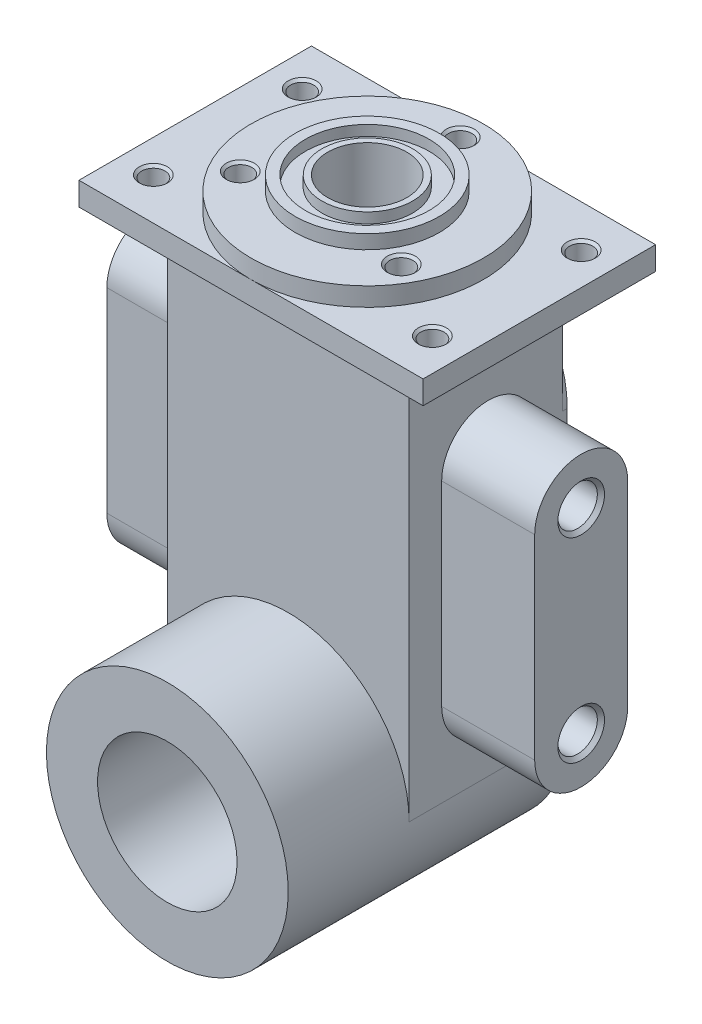
SolidWorks part; units mm, degrees
ref_plane "前视基准面" through (0, 0, 0) normal (0, 0, 1) x (1, 0, 0)
ref_plane "上视基准面" through (0, 0, 0) normal (0, 1, 0) x (1, 0, 0)
ref_plane "右视基准面" through (0, 0, 0) normal (1, 0, 0) x (0, 0, -1)
sketch "草图1" plane through (0, 0, 0) normal (0, 0, 1) x (1, 0, 0)
  line L0 (0, 0) -> (0, 60) construction
  line L1 (0, -55) -> (0, 55) construction
  line L2 (-26, 0) -> (-26, 60)
  line L3 (26, 0) -> (26, 60)
  arc A0 (-26, 0) -> (26, 0) centre (0, 0) ccw
  arc A1 (26, 60) -> (-26, 60) centre (0, 60) ccw
  point P5 (0, 30)
  dimension "D1" = 52
  dimension "D2" = 60
extrude "凸台-拉伸1" add sketch "草图1" along normal blind 34
sketch "草图3" plane through (0, 0, 0) normal (0, 0, 1) x (1, 0, 0)
  line L1 (-26, 60) -> (26, 60)
  line L2 (-26, 60) -> (-26, 87)
  line L3 (-26, 87) -> (26, 87)
  line L4 (26, 60) -> (26, 87)
  arc A0 (26, 60) -> (-26, 60) centre (0, 60) ccw construction
  point P4 (0, 0)
  dimension "D1" = 27
sketch "草图4" plane through (0, 0, 0) normal (0, 1, 0) x (1, 0, 0)
  line L0 (0, -18.7) -> (0, 18.7) construction
  line L1 (-37, -42) -> (37, -42)
  line L2 (-37, -42) -> (-37, 8)
  line L3 (-37, 8) -> (37, 8)
  line L4 (37, -42) -> (37, 8)
  line L5 (-37, -42) -> (37, 8) construction
  line L6 (-37, 8) -> (37, -42) construction
  line L7 (-26, 0) -> (26, 0) construction
  point P0 (0, -17)
  dimension "D1" = 74
  dimension "D2" = 50
  dimension "D3" = 17
extrude "凸台-拉伸2" add sketch "草图4" along normal blind 5 from offset 87 separate body
sketch "草图5" plane through (0, 92, 0) normal (0, 1, 0) x (1, 0, 0)
  line L0 (0, -37.4) -> (0, 37.4) construction
  line L1 (37, 8) -> (-37, 8) construction
  line L2 (-37, -42) -> (37, -42) construction
  circle A0 centre (0, -17) radius 25
extrude "凸台-拉伸3" add sketch "草图5" along normal blind 4
sketch "草图6" plane through (0, 96, 0) normal (0, 1, 0) x (1, 0, 0)
  circle A0 centre (0, -17) radius 15.5
  dimension "D1" = 31
extrude "凸台-拉伸4" add sketch "草图6" along normal blind 3
sketch "草图7" plane through (0, 0, 0) normal (1, 0, 0) x (0, 0, -1)
  line L0 (-17, 60) -> (-17, 18) construction
  line L1 (0, 50.6) -> (0, -50.6) construction
  line L2 (-27, 60) -> (-27, 18)
  line L3 (-7, 60) -> (-7, 18)
  line L4 (-34, 60) -> (0, 60) construction
  arc A0 (-27, 60) -> (-7, 60) centre (-17, 60) cw
  arc A1 (-27, 18) -> (-7, 18) centre (-17, 18) ccw
  dimension "D1" = 42
  dimension "D2" = 17
  dimension "D3" = 10
  dimension "D4" = 10
extrude "凸台-拉伸5" add sketch "草图7" along normal mid plane 92
sketch "草图8" plane through (0, 0, 34) normal (0, 0, 1) x (1, 0, 0)
  line L0 (-37, 87) -> (37, 87) construction
  line L1 (-26, 60) -> (26, 60)
  line L2 (-26, 60) -> (-26, 87)
  line L3 (-26, 87) -> (26, 87)
  line L4 (26, 60) -> (26, 87)
  arc A0 (26, 60) -> (-26, 60) centre (0, 60) ccw construction
  point P7 (26, 60)
extrude "凸台-拉伸6" add sketch "草图8" against normal blind 33
sketch "草图9" plane through (0, 0, 34) normal (0, 0, 1) x (1, 0, 0)
  circle A0 centre (0, 0) radius 26
  dimension "D1" = 52
extrude "凸台-拉伸7" add sketch "草图9" along normal blind 60 from surface at -34 starting at face at (0, 30, 0)
sketch "草图10" plane through (0, 0, 0) normal (0, 0, -1) x (-1, 0, 0)
  line L0 (0, 0) -> (0, 60) construction
  line L1 (-16, 0) -> (-16, 60)
  line L2 (16, 0) -> (16, 60)
  arc A0 (-16, 0) -> (16, 0) centre (0, 0) ccw
  arc A1 (16, 60) -> (-16, 60) centre (0, 60) ccw
  point P4 (0, 30)
extrude "切除-拉伸1" cut sketch "草图10" against normal blind 30
sketch "草图11" plane through (0, 0, 60) normal (0, 0, 1) x (1, 0, 0)
  circle A0 centre (0, 0) radius 15
  dimension "D1" = 30
extrude "切除-拉伸2" cut sketch "草图11" against normal through all
sketch "草图12" plane through (0, 99, 0) normal (0, 1, 0) x (1, 0, 0)
  circle A0 centre (0, -17) radius 8.5
  dimension "D1" = 17
extrude "切除-拉伸3" cut sketch "草图12" against normal up to next
sketch "草图13" plane through (0, 99, 0) normal (0, 1, 0) x (1, 0, 0)
  circle A0 centre (0, -17) radius 9.75
  circle A1 centre (0, -17) radius 13.3
  dimension "D1" = 19.5
  dimension "D2" = 26.6
extrude "切除-拉伸4" cut sketch "草图13" against normal blind 2.25
sketch "草图14" plane through (0, 96, 0) normal (0, 1, 0) x (1, 0, 0)
  circle A0 centre (0, -17) radius 20 construction
  point P3 (0, 3)
  dimension "D1" = 40
hole_wizard "M6 螺纹孔1" positions "草图14" profile "草图15" tap size "M6" standard "GB" end condition up to next
sketch "草图15" plane through (0, 96, -3) normal (1, 0, 0) x (0, 0, 1)
  line L0 (0, 0) -> (0, 9)
  line L1 (0, 9) -> (2.5, 9)
  line L2 (2.5, 9) -> (2.5, 0.525)
  line L3 (2.5, 0.525) -> (3.025, 0)
  line L5 (3.025, 0) -> (0, 0)
  line L6 (-2.5, 0.525) -> (-3.025, 0) construction
  line L11 (0, -6.35) -> (0, 107.95) construction
  dimension "通孔螺纹孔钻头直径" = 5
  dimension "通孔螺纹孔钻头深度" = 9
  dimension "近端锥形沉头孔直径" = 6.05
  dimension "近端锥形沉头孔角度" = 90
cosmetic thread "孔螺纹线1" parameters "D2"=6
sketch "草图16" plane through (0, 96, 0) normal (0, 1, 0) x (1, 0, 0)
  line L0 (-17.3205, -27) -> (0, -17) construction
  line L1 (0, -17) -> (17.3205, -27) construction
  line L2 (-17.3205, -27) -> (17.3205, -27) construction
  circle A0 centre (0, -17) radius 20 construction
  point P3 (-17.3205, -27)
  point P4 (17.3205, -27)
  dimension "D1" = 40
  dimension "D2" = 120
hole_wizard "M6 螺纹孔2" positions "草图16" profile "草图17" tap size "M6" standard "GB"
sketch "草图17" plane through (17.3205, 96, 27) normal (1, 0, 0) x (0, 0, 1)
  line L0 (0, 0) -> (0, 16)
  line L1 (0, 16) -> (2.5, 14.4978)
  line L2 (2.5, 14.4978) -> (2.5, 0.525)
  line L3 (2.5, 0.525) -> (3.025, 0)
  line L5 (3.025, 0) -> (0, 0)
  line L6 (-2.5, 0.525) -> (-3.025, 0) construction
  line L10 (0, 16) -> (-2.5, 14.4978) construction
  line L11 (0, -6.35) -> (0, 107.95) construction
  dimension "螺纹孔钻头直径" = 5
  dimension "螺纹孔钻头深度" = 16
  dimension "近端锥形沉头孔直径" = 6.05
  dimension "近端锥形沉头孔角度" = 90
  dimension "导头角度" = 118
cosmetic thread "孔螺纹线2" parameters "D1"=12, "D2"=6
cosmetic thread "孔螺纹线3" parameters "D1"=12, "D2"=6
sketch "草图18" plane through (0, 92, 0) normal (0, 1, 0) x (1, 0, 0)
  line L0 (0, -37.4) -> (0, 37.4) construction
  line L1 (-30, -33) -> (30, -33) construction
  line L2 (-30, -33) -> (-30, -1) construction
  line L3 (-30, -1) -> (30, -1) construction
  line L4 (30, -33) -> (30, -1) construction
  line L5 (-30, -33) -> (30, -1) construction
  line L6 (-30, -1) -> (30, -33) construction
  circle A0 centre (0, -17) radius 15.5 construction
  point P0 (0, -17)
  point P10 (-30, -1)
  point P11 (-30, -33)
  point P12 (30, -33)
  point P13 (30, -1)
  dimension "D1" = 32
  dimension "D2" = 60
hole_wizard "M6 螺纹孔3" positions "草图18" profile "草图19" tap size "M6" standard "GB" end condition up to next
sketch "草图19" plane through (30, 92, 1) normal (1, 0, 0) x (0, 0, 1)
  line L0 (0, 0) -> (0, 5)
  line L1 (0, 5) -> (2.5, 5)
  line L2 (2.5, 5) -> (2.5, 0.525)
  line L3 (2.5, 0.525) -> (3.025, 0)
  line L5 (3.025, 0) -> (0, 0)
  line L6 (-2.5, 0.525) -> (-3.025, 0) construction
  line L11 (0, -6.35) -> (0, 107.95) construction
  dimension "通孔螺纹孔钻头直径" = 5
  dimension "通孔螺纹孔钻头深度" = 5
  dimension "近端锥形沉头孔直径" = 6.05
  dimension "近端锥形沉头孔角度" = 90
cosmetic thread "孔螺纹线4" parameters "D2"=6
cosmetic thread "孔螺纹线5" parameters "D2"=6
cosmetic thread "孔螺纹线6" parameters "D2"=6
cosmetic thread "孔螺纹线7" parameters "D2"=6
sketch "草图20" plane through (46, 0, 0) normal (1, 0, 0) x (0, 0, -1)
  point P0 (-17, 60)
  point P1 (-17, 18)
hole_wizard "M10 螺纹孔1" positions "草图20" profile "草图21" tap size "M10" standard "GB"
sketch "草图21" plane through (46, 60, 17) normal (0, 1, 0) x (0, 0, -1)
  line L0 (0, 0) -> (0, 22)
  line L1 (0, 22) -> (4.25, 19.4463)
  line L2 (4.25, 19.4463) -> (4.25, 0.775)
  line L3 (4.25, 0.775) -> (5.025, 0)
  line L5 (5.025, 0) -> (0, 0)
  line L6 (-4.25, 0.775) -> (-5.025, 0) construction
  line L10 (0, 22) -> (-4.25, 19.4463) construction
  line L11 (0, -6.35) -> (0, 107.95) construction
  dimension "螺纹孔钻头直径" = 8.5
  dimension "螺纹孔钻头深度" = 22
  dimension "近端锥形沉头孔直径" = 10.05
  dimension "近端锥形沉头孔角度" = 90
  dimension "导头角度" = 118
cosmetic thread "孔螺纹线8" parameters "D1"=18, "D2"=10
cosmetic thread "孔螺纹线9" parameters "D1"=18, "D2"=10
mirror "镜向1" about plane through (0, 0, 0) normal (1, 0, 0) of "M10 螺纹孔1"
cosmetic thread "孔螺纹线10" parameters "D1"=18, "D2"=10
cosmetic thread "孔螺纹线11" parameters "D1"=18, "D2"=10
